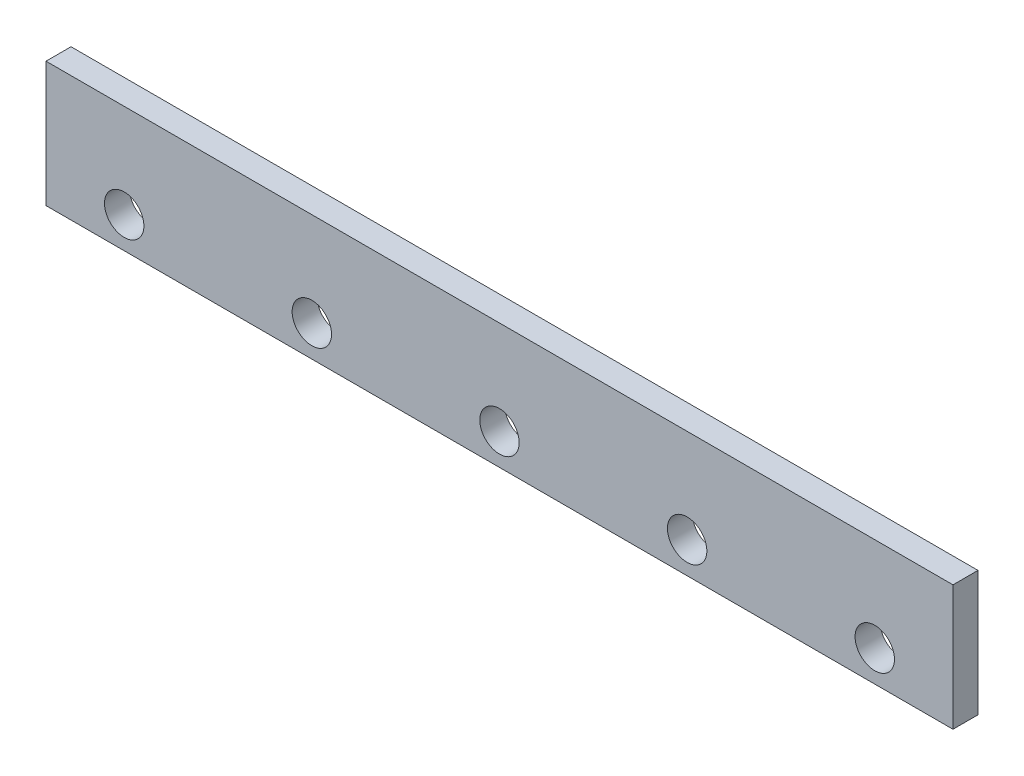
SolidWorks part; units mm, degrees
ref_plane "Front Plane" through (0, 0, 0) normal (0, 0, 1) x (1, 0, 0)
ref_plane "Top Plane" through (0, 0, 0) normal (0, 1, 0) x (1, 0, 0)
ref_plane "Right Plane" through (0, 0, 0) normal (1, 0, 0) x (0, 0, -1)
sketch "Sketch1" plane through (0, 0, 0) normal (0, 0, 1) x (1, 0, 0)
  line L1 (290, -40) -> (-290, -40)
  line L2 (290, -40) -> (290, 40)
  line L3 (290, 40) -> (-290, 40)
  line L4 (-290, -40) -> (-290, 40)
  line L5 (290, -40) -> (-290, 40) construction
  line L6 (290, 40) -> (-290, -40) construction
  point P0 (0, 0)
  dimension "D1" = 580
  dimension "D2" = 80
extrude "Boss-Extrude1" add sketch "Sketch1" along normal mid plane 16
sketch "Sketch2" plane through (0, 0, 8) normal (0, 0, 1) x (1, 0, 0)
  line L0 (-290, -40) -> (-290, -20) construction
  line L1 (-290, 40) -> (-290, -40) construction
  line L2 (-290, -20) -> (-240, -20) construction
  line L3 (-240, -20) -> (-120, -20) construction
  line L4 (-120, -20) -> (0, -20) construction
  line L5 (0, -20) -> (83.9651, -20) construction
  line L6 (83.9651, -20) -> (157.2346, -20) construction
  line L7 (157.2346, -20) -> (211.7526, -20) construction
  line L8 (0, -40) -> (0, 40) construction
  line L9 (-290, -40) -> (290, -40) construction
  line L10 (290, 40) -> (-290, 40) construction
  circle A0 centre (-240, -20) radius 12.6
  circle A1 centre (-120, -20) radius 12.6
  circle A2 centre (0, -20) radius 12.6
  circle A3 centre (120, -20) radius 12.6
  circle A4 centre (240, -20) radius 12.6
  dimension "D5" = 25.2
  dimension "D6" = 25.2
  dimension "D7" = 25.2
  dimension "D1" = 20
  dimension "D2" = 50
  dimension "D3" = 120
  dimension "D4" = 120
extrude "Cut-Extrude1" cut sketch "Sketch2" against normal through all
